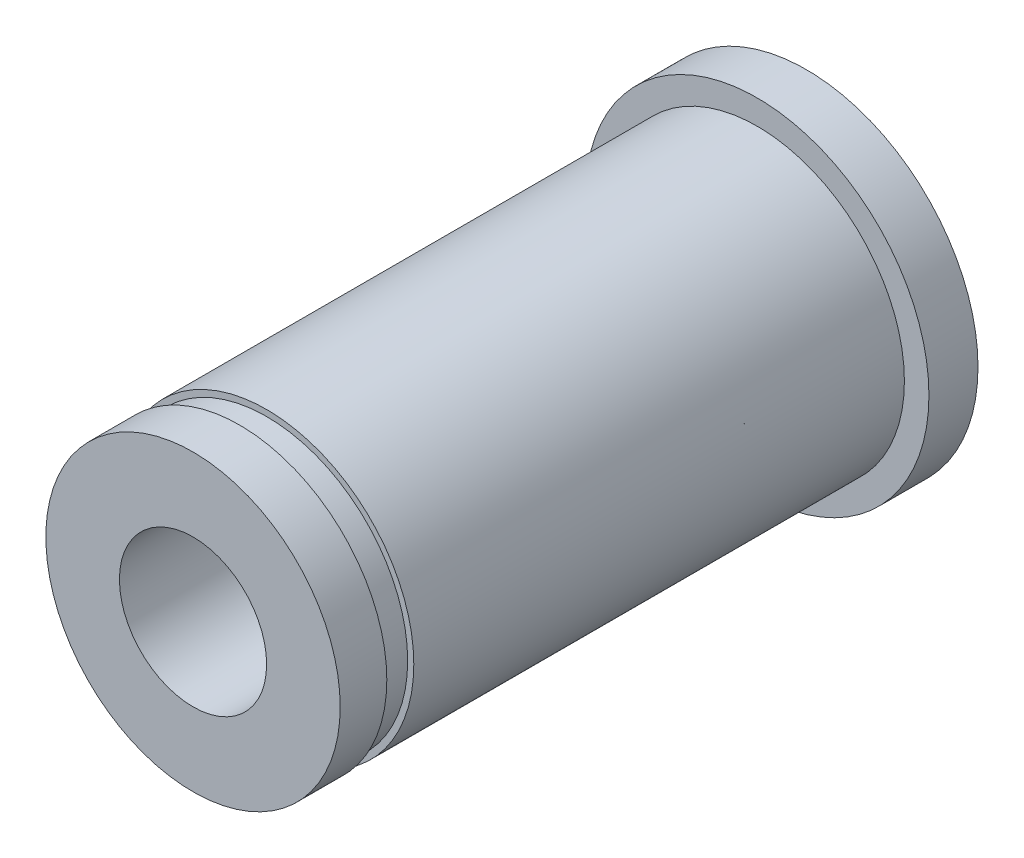
SolidWorks part; units mm, degrees
material "AISI 1045 钢，冷拔"
ref_plane "前视基准面" through (0, 0, 0) normal (0, 0, 1) x (1, 0, 0)
ref_plane "上视基准面" through (0, 0, 0) normal (0, 1, 0) x (1, 0, 0)
ref_plane "右视基准面" through (0, 0, 0) normal (1, 0, 0) x (0, 0, -1)
sketch "草图1" plane through (0, 0, 0) normal (0, 0, 1) x (1, 0, 0)
  circle A0 centre (0, 0) radius 6
  dimension "D1" = 12
extrude "凸台-拉伸1" add sketch "草图1" along normal blind 23
sketch "草图2" plane through (0, 0, 0) normal (0, 0, -1) x (-1, 0, 0)
  circle A0 centre (0, 0) radius 7
  dimension "D1" = 14
extrude "凸台-拉伸2" add sketch "草图2" along normal blind 2
sketch "草图3" plane through (0, 0, 0) normal (0, 1, 0) x (1, 0, 0)
  line L0 (-6, 0) -> (-6, -20) construction
  line L1 (0, -23) -> (0, -12.3222) construction
  line L2 (-6, -20) -> (-5.75, -20)
  line L3 (-6, -20) -> (-6, -21.1)
  line L4 (-6, -21.1) -> (-5.75, -21.1)
  line L5 (-5.75, -20) -> (-5.75, -21.1)
  line L6 (-6, -23) -> (6, -23) construction
  dimension "D1" = 20
  dimension "D2" = 1.1
  dimension "D3" = 0.25
revolve "切除-旋转1" cut sketch "草图3" angle 360 about L1
sketch "草图4" plane through (0, 0, -2) normal (0, 0, -1) x (-1, 0, 0)
  circle A0 centre (0, 0) radius 3
  dimension "D1" = 6
extrude "切除-拉伸1" cut sketch "草图4" against normal blind 27
